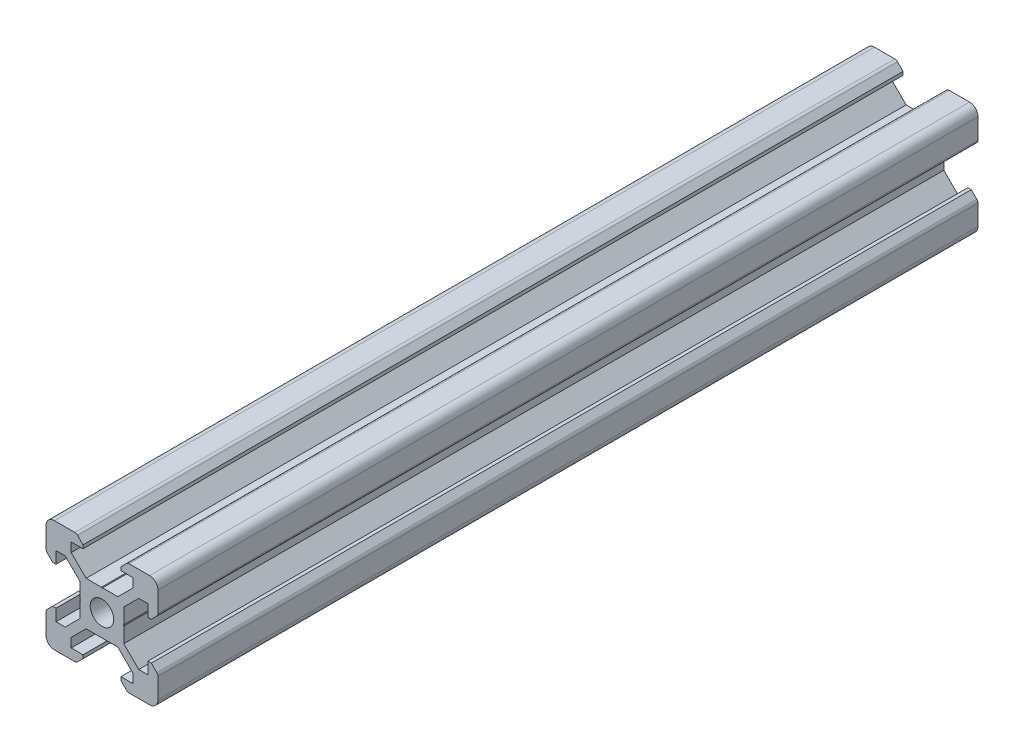
SolidWorks part; units mm, degrees
ref_plane "Front" through (0, 0, 0) normal (0, 0, 1) x (1, 0, 0)
ref_plane "Top" through (0, 0, 0) normal (0, 1, 0) x (1, 0, 0)
ref_plane "Right" through (0, 0, 0) normal (1, 0, 0) x (0, 0, -1)
sketch "Sketch1" plane through (0, 0, 0) normal (0, 0, 1) x (1, 0, 0)
  line L0 (-8.5, 10) -> (-10, 8.5) construction
  line L1 (-8.5, 10) -> (-4.8628, 10)
  line L2 (-10, 8.5) -> (-10, 4.8628)
  line L3 (-8.5, -10) -> (-4.8628, -10)
  line L4 (10, 8.5) -> (10, 4.8628)
  line L5 (-10, 10) -> (10, -10) construction
  line L6 (-10, -10) -> (10, 10) construction
  line L7 (-5.5, -8.2) -> (-3.3865, -8.2)
  line L8 (-8.2, -5.5) -> (-8.2, -3.3865)
  line L9 (-5.5, 8.2) -> (-3.3865, 8.2)
  line L10 (8.2, -5.5) -> (8.2, -3.3865)
  line L11 (-3.9005, 2.8395) -> (-6.561, 5.5)
  line L12 (-6.561, 5.5) -> (-8.2, 5.5)
  line L13 (-2.8395, -3.9005) -> (-0.1, -3.9005)
  line L14 (-3.9005, -2.8395) -> (-3.9005, -0.1)
  line L15 (-2.8395, 3.9005) -> (-0.1, 3.9005)
  line L16 (3.9005, -2.8395) -> (3.9005, -0.1)
  line L17 (-8.2, 3.3865) -> (-8.81, 3.3865)
  line L18 (-8.81, 3.3865) -> (-9.7976, 4.3741)
  line L19 (8.5, 10) -> (10, 8.5) construction
  line L20 (-2.8395, 3.9005) -> (-5.5, 6.561)
  line L21 (-5.5, 6.561) -> (-5.5, 8.2)
  line L22 (-3.3865, 8.2) -> (-3.3865, 8.81)
  line L23 (-3.3865, 8.81) -> (-4.3741, 9.7976)
  line L24 (0, 24.069) -> (0, -33.8154) construction
  line L25 (3.3865, 8.81) -> (4.3741, 9.7976)
  line L26 (3.3865, 8.2) -> (3.3865, 8.81)
  line L27 (5.5, 6.561) -> (5.5, 8.2)
  line L28 (2.8395, 3.9005) -> (5.5, 6.561)
  line L29 (3.3865, 8.2) -> (5.5, 8.2)
  line L30 (4.8628, 10) -> (8.5, 10)
  line L31 (-0.1, 3.9005) -> (0, 3.8005)
  line L32 (0.1, 3.9005) -> (0, 3.8005)
  line L33 (0.1, 3.9005) -> (2.8395, 3.9005)
  line L34 (25.9287, 0) -> (-28.3459, 0) construction
  line L35 (-0.1, -3.9005) -> (0, -3.8005)
  line L36 (0.1, -3.9005) -> (0, -3.8005)
  line L37 (0.1, -3.9005) -> (2.8395, -3.9005)
  line L38 (-3.9005, 0.1) -> (-3.8005, 0)
  line L39 (-3.8005, 0) -> (-3.9005, -0.1)
  line L40 (-3.9005, 0.1) -> (-3.9005, 2.8395)
  line L41 (3.9005, 0.1) -> (3.8005, 0)
  line L42 (3.8005, 0) -> (3.9005, -0.1)
  line L43 (3.9005, 0.1) -> (3.9005, 2.8395)
  line L44 (8.81, 3.3865) -> (9.7976, 4.3741)
  line L45 (8.2, 3.3865) -> (8.81, 3.3865)
  line L46 (6.561, 5.5) -> (8.2, 5.5)
  line L47 (3.9005, 2.8395) -> (6.561, 5.5)
  line L48 (2.8395, -3.9005) -> (5.5, -6.561)
  line L49 (3.9005, -2.8395) -> (6.561, -5.5)
  line L50 (-2.8395, -3.9005) -> (-5.5, -6.561)
  line L51 (-3.9005, -2.8395) -> (-6.561, -5.5)
  line L52 (6.561, -5.5) -> (8.2, -5.5)
  line L53 (-6.561, -5.5) -> (-8.2, -5.5)
  line L54 (-8.81, -3.3865) -> (-9.7976, -4.3741)
  line L55 (-8.2, -3.3865) -> (-8.81, -3.3865)
  line L56 (8.81, -3.3865) -> (9.7976, -4.3741)
  line L57 (8.2, -3.3865) -> (8.81, -3.3865)
  line L58 (8.2, 3.3865) -> (8.2, 5.5)
  line L59 (10, -4.8628) -> (10, -8.5)
  line L60 (-8.2, 3.3865) -> (-8.2, 5.5)
  line L61 (-10, -4.8628) -> (-10, -8.5)
  line L62 (-3.3865, -8.81) -> (-4.3741, -9.7976)
  line L63 (-3.3865, -8.2) -> (-3.3865, -8.81)
  line L64 (3.3865, -8.81) -> (4.3741, -9.7976)
  line L65 (3.3865, -8.2) -> (3.3865, -8.81)
  line L66 (-5.5, -6.561) -> (-5.5, -8.2)
  line L67 (5.5, -6.561) -> (5.5, -8.2)
  line L68 (3.3865, -8.2) -> (5.5, -8.2)
  line L69 (4.8628, -10) -> (8.5, -10)
  circle A0 centre (0, 0) radius 2.1
  arc A1 (-8.5, 10) -> (-10, 8.5) centre (-8.5, 8.5) ccw
  arc A2 (10, 8.5) -> (8.5, 10) centre (8.5, 8.5) ccw
  arc A3 (-4.3741, 9.7976) -> (-4.8628, 10) centre (-4.8628, 9.3088) ccw
  arc A4 (4.8628, 10) -> (4.3741, 9.7976) centre (4.8628, 9.3088) ccw
  arc A5 (-8.5, -10) -> (-10, -8.5) centre (-8.5, -8.5) cw
  arc A6 (9.7976, 4.3741) -> (10, 4.8628) centre (9.3088, 4.8628) ccw
  arc A7 (-10, 4.8628) -> (-9.7976, 4.3741) centre (-9.3088, 4.8628) ccw
  arc A8 (-10, -4.8628) -> (-9.7976, -4.3741) centre (-9.3088, -4.8628) cw
  arc A9 (9.7976, -4.3741) -> (10, -4.8628) centre (9.3088, -4.8628) cw
  arc A10 (10, -8.5) -> (8.5, -10) centre (8.5, -8.5) cw
  arc A11 (-4.3741, -9.7976) -> (-4.8628, -10) centre (-4.8628, -9.3088) cw
  arc A12 (4.8628, -10) -> (4.3741, -9.7976) centre (4.8628, -9.3088) cw
  point P17 (-9.25, 9.25)
  point P21 (9.25, 9.25)
  dimension "D2" = 4.2
  dimension "D4" = 1.5
  dimension "D3" = 20
  dimension "D5" = 0.529
  dimension "D6" = 6.773
  dimension "D7" = 90
  dimension "D8" = 11
  dimension "D9" = 0.61
  dimension "D10" = 0.1
  dimension "D11" = 0.1
  dimension "D12" = 0.1
  dimension "D13" = 0.1
  dimension "D14" = 5.679
  dimension "D15" = 1.639
  dimension "D16" = 1.8
  dimension "D17" = 90
  dimension "D18" = 6.773
  dimension "D19" = 90
extrude "Boss-Extrude1" add sketch "Sketch1" along normal blind 146.5
